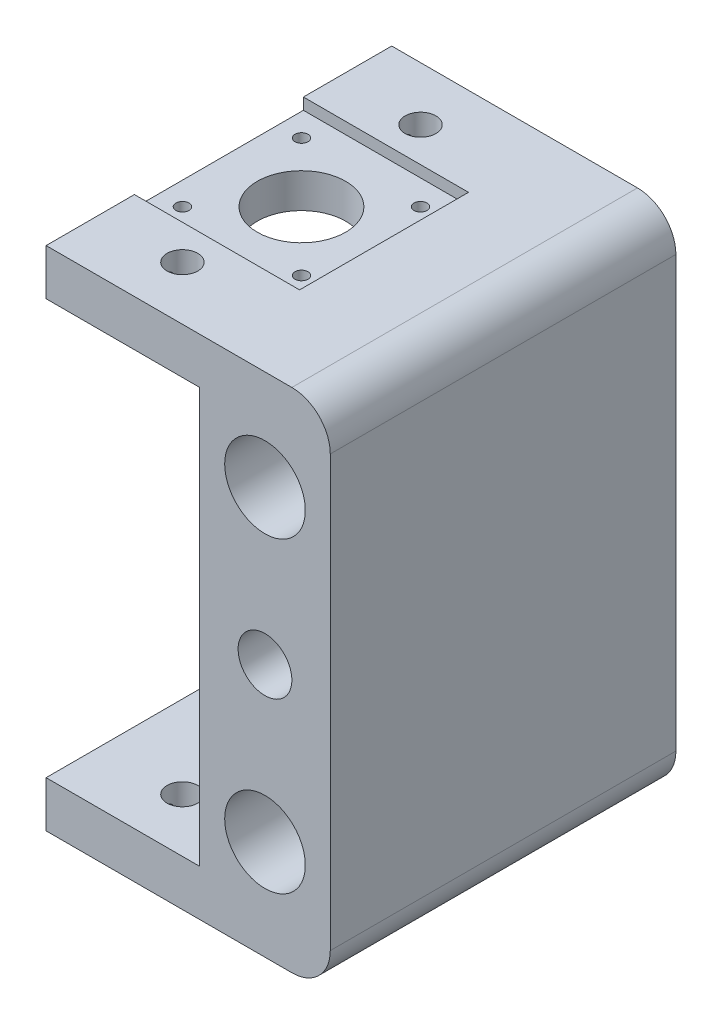
SolidWorks part; units mm, degrees
ref_plane "Front Plane" through (0, 0, 0) normal (0, 0, 1) x (1, 0, 0)
ref_plane "Top Plane" through (0, 0, 0) normal (0, 1, 0) x (1, 0, 0)
ref_plane "Right Plane" through (0, 0, 0) normal (1, 0, 0) x (0, 0, -1)
sketch "Sketch1" plane through (0, 0, 0) normal (0, 0, 1) x (1, 0, 0)
  line L0 (0, 0) -> (64, 0)
  line L1 (74, 10) -> (74, 122)
  line L2 (64, 132) -> (0, 132)
  line L3 (0, 132) -> (0, 120)
  line L4 (0, 120) -> (40, 120)
  line L5 (40, 120) -> (40, 12)
  line L6 (40, 12) -> (0, 12)
  line L7 (0, 12) -> (0, 0)
  line L8 (0, 0) -> (0, 12) construction
  line L9 (0, 120) -> (0, 132) construction
  arc A0 (64, 0) -> (74, 10) centre (64, 10) ccw
  arc A1 (74, 122) -> (64, 132) centre (64, 122) ccw
  circle A2 centre (57, 106) radius 10.5
  circle A3 centre (57, 66) radius 7
  circle A4 centre (57, 26) radius 10.5
  point P3 (0, 126)
  point P12 (74, 0)
  point P15 (74, 132)
  dimension "D6" = 10
  dimension "D7" = 21
  dimension "D8" = 40
  dimension "14" = 14
  dimension "D12" = 21
  dimension "D1" = 12
  dimension "D2" = 132
  dimension "D3" = 74
  dimension "D4" = 40
  dimension "D5" = 12
  dimension "D9" = 40
  dimension "D10" = 26
  dimension "D11" = 17
  dimension "D13" = 26
extrude "Boss-Extrude1" add sketch "Sketch1" along normal blind 90
sketch "Sketch2" plane through (0, 0, 0) normal (0, 0, -1) x (-1, 0, 0)
  circle A0 centre (-57, 66) radius 11.5
  dimension "D1" = 23
extrude "Cut-Extrude1" cut sketch "Sketch2" against normal blind 6
sketch "Sketch3" plane through (0, 0, 6) normal (0, 0, -1) x (-1, 0, 0)
  line L0 (-57, 66) -> (-57, 74) construction
  circle A0 centre (-57, 74) radius 1.5
  circle A1 centre (-49, 66) radius 1.5
  circle A2 centre (-57, 58) radius 1.5
  circle A3 centre (-65, 66) radius 1.5
  point P13 (-57, 66)
  dimension "D1" = 3
  dimension "D2" = 8
  dimension "D3" = 4
extrude "Cut-Extrude2" cut sketch "Sketch3" against normal blind 40
sketch "Sketch4" plane through (0, 132, 0) normal (0, 1, 0) x (1, 0, 0)
  line L0 (0, -90) -> (0, 0) construction
  line L1 (0, -23) -> (43, -23)
  line L2 (0, -23) -> (0, -67)
  line L3 (0, -67) -> (43, -67)
  line L4 (43, -23) -> (43, -67)
  line L6 (64, 0) -> (0, 0) construction
  point P8 (0, -45)
  dimension "D1" = 43
  dimension "D2" = 44
  dimension "D3" = 45
extrude "Cut-Extrude3" cut sketch "Sketch4" against normal blind 3
sketch "Sketch5" plane through (0, 129, 0) normal (0, 1, 0) x (1, 0, 0)
  line L0 (0, -23) -> (0, -67) construction
  line L1 (43, -23) -> (0, -23) construction
  circle A0 centre (21.5, -45) radius 11.5
  point P4 (0, -45)
  dimension "D1" = 23
  dimension "D2" = 21.5
  dimension "D3" = 22
extrude "Cut-Extrude4" cut sketch "Sketch5" against normal up to surface (9 mm away) up to face at (20, 120, 45)
sketch "Sketch8" plane through (0, 120, 0) normal (0, -1, 0) x (-1, 0, 0)
  circle A0 centre (-21.5, -45) radius 11.5 construction
  point P0 (-6, -29.5)
  dimension "D1" = 15.5
  dimension "D2" = 15.5
hole_wizard "CBORE for M3 Pan Head Screw1" positions "Sketch8" profile "Sketch7" counterbore size "M3" standard "ISO"
sketch "Sketch7" plane through (6, 120, 29.5) normal (1, 0, 0) x (0, 0, -1)
  line L0 (0, 0) -> (0, 21.0215)
  line L1 (0, 21.0215) -> (1.7, 20)
  line L2 (1.7, 20) -> (1.7, 3)
  line L3 (1.7, 3) -> (2.75, 3)
  line L4 (2.75, 3) -> (2.75, 0)
  line L5 (2.75, 0) -> (0, 0)
  line L10 (0, 21.0215) -> (-1.7, 20) construction
  line L11 (0, -6.35) -> (0, 107.95) construction
  dimension "Hole Dia." = 3.4
  dimension "Hole Depth" = 20
  dimension "C'Bore Dia." = 5.5
  dimension "C'Bore Depth" = 3
  dimension "Drill Angle" = 118
pattern_circular "CirPattern1" count 4 every 90 about axis through (21.5, 0, 45) along (0, 1, 0) of "CBORE for M3 Pan Head Screw1"
sketch "Sketch9" plane through (0, 132, 0) normal (0, 1, 0) x (1, 0, 0)
  line L0 (21.5, -76) -> (21.5, -14) construction
  line L1 (64, 0) -> (0, 0) construction
  circle A0 centre (21.5, -14) radius 4
  circle A1 centre (21.5, -76) radius 4
  circle A2 centre (21.5, -45) radius 11.5 construction
  circle A3 centre (21.5, -45) radius 5
  point P8 (21.5, -45)
  point P10 (21.5, -76)
  dimension "D2" = 8
  dimension "D3" = 10
  dimension "D1" = 14
extrude "Cut-Extrude5" cut sketch "Sketch9" against normal through all
sketch "Sketch10" plane through (0, 12, 0) normal (0, 1, 0) x (1, 0, 0)
  circle A0 centre (21.5, -45) radius 12
  dimension "24" = 24
extrude "Cut-Extrude6" cut sketch "Sketch10" against normal blind 8
sketch "Sketch13" plane through (0, 0, 0) normal (-1, 0, 0) x (0, 0, 1)
  line L0 (10, 126) -> (18, 126) construction
  line L1 (10, 132) -> (10, 120) construction
  line L2 (18, 120) -> (18, 132) construction
  line L3 (72, 6) -> (80, 6) construction
  line L4 (72, 12) -> (72, 0) construction
  line L5 (80, 0) -> (80, 12) construction
  point P0 (14, 126)
  point P2 (76, 126)
  point P4 (76, 6)
  point P6 (14, 6)
hole_wizard "M4 Tapped Hole1" positions "Sketch13" profile "Sketch12" tap size "M4" standard "ISO"
sketch "Sketch12" plane through (0, 126, 14) normal (0, 1, 0) x (0, 0, 1)
  line L0 (0, 0) -> (0, 20)
  line L1 (0, 20) -> (1.65, 19.0086)
  line L2 (1.65, 19.0086) -> (1.65, 0)
  line L5 (1.65, 0) -> (0, 0)
  line L10 (0, 20) -> (-1.65, 19.0086) construction
  line L11 (0, -6.35) -> (0, 107.95) construction
  dimension "Tap Drill Dia." = 3.3
  dimension "Tap Drill Depth" = 20
  dimension "Drill Angle" = 118
cosmetic thread "Hole Thread1" parameters "D1"=8, "D2"=4
cosmetic thread "Hole Thread2" parameters "D1"=8, "D2"=4
cosmetic thread "Hole Thread3" parameters "D1"=8, "D2"=4
cosmetic thread "Hole Thread4" parameters "D1"=8, "D2"=4
